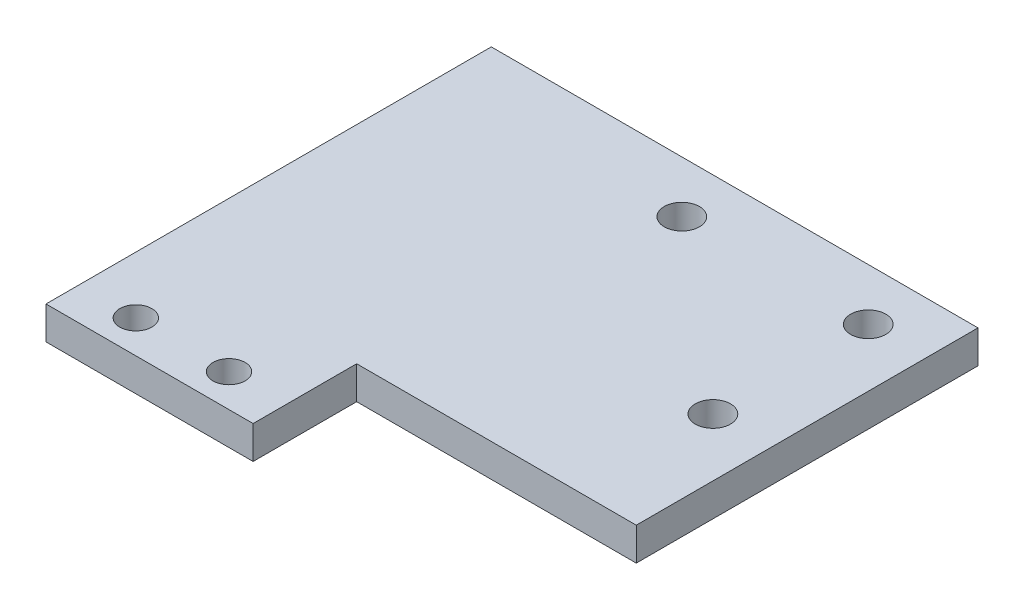
SolidWorks part; units mm, degrees
material "6061 Alloy"
ref_plane "Front Plane" through (0, 0, 0) normal (0, 0, 1) x (1, 0, 0)
ref_plane "Top Plane" through (0, 0, 0) normal (0, 1, 0) x (1, 0, 0)
ref_plane "Right Plane" through (0, 0, 0) normal (1, 0, 0) x (0, 0, -1)
sketch "Sketch1" plane through (0, 0, 0) normal (0, 1, 0) x (1, 0, 0)
  line L0 (0, 0) -> (0, 43)
  line L1 (0, 43) -> (47, 43)
  line L2 (47, 43) -> (47, 10)
  line L3 (47, 10) -> (20, 10)
  line L4 (20, 10) -> (20, 0)
  line L5 (0, 0) -> (20, 0)
  line L16 (20, 0) -> (20, 6.35) construction
  line L17 (14.5, 3.175) -> (5.5, 3.175) construction
  circle A6 centre (14.5, 3.175) radius 1.55
  circle A9 centre (5.5, 3.175) radius 1.55
  circle A12 centre (41.4, 23) radius 1.7 construction
  circle A13 centre (41.4, 38) radius 1.7 construction
  circle A14 centre (23.4, 38) radius 1.7 construction
  circle A15 centre (41.4, 23) radius 1.7
  circle A16 centre (41.4, 38) radius 1.7
  circle A17 centre (23.4, 38) radius 1.7
  point P8 (0, 0)
  point P9 (41.4, 23)
  point P20 (10, 3.175)
  point P21 (10, 0)
  dimension "D2" = 3.1
  dimension "D3" = 3.1
  dimension "D1" = 33
  dimension "D9" = 47
  dimension "D11" = 10
  dimension "D4" = 9
  dimension "D5" = 3.175
extrude "Boss-Extrude1" add sketch "Sketch1" along normal blind 3.175
equation "\"D3@Sketch1\"=\"D2@Sketch1\""
